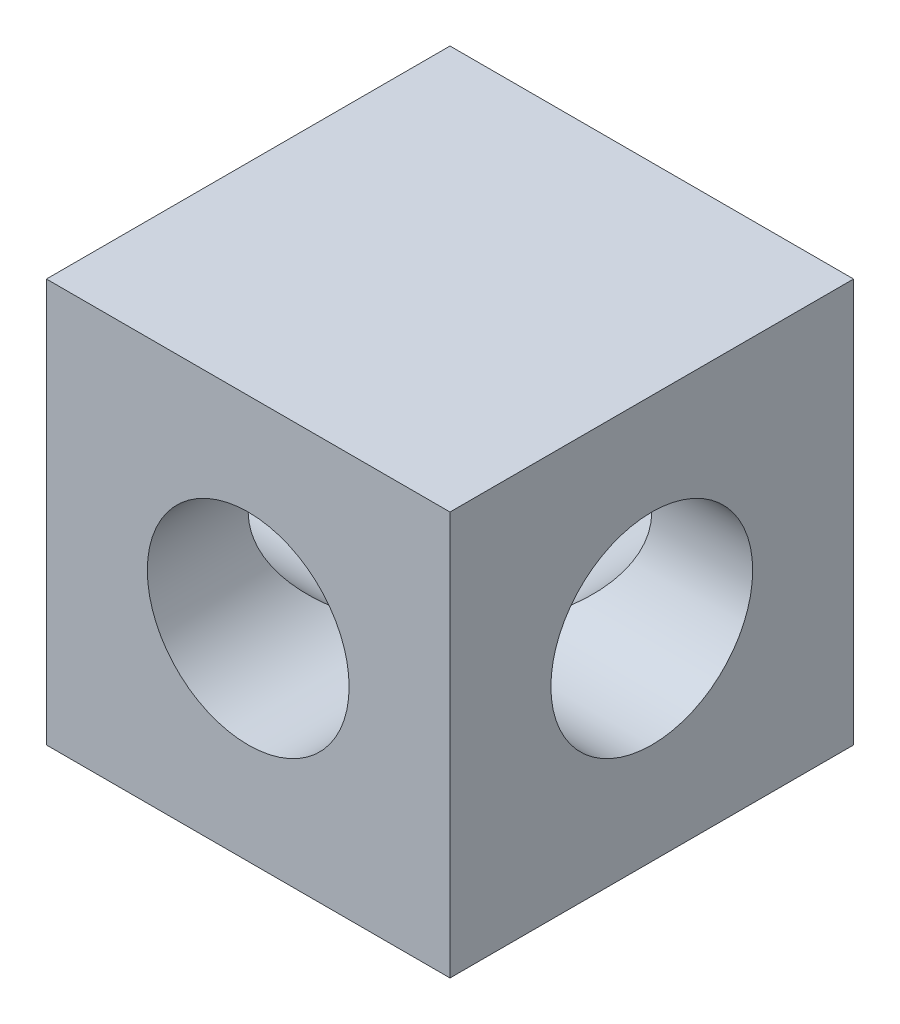
SolidWorks part; units mm, degrees
ref_plane "Front" through (0, 0, 0) normal (0, 0, 1) x (1, 0, 0)
ref_plane "Top" through (0, 0, 0) normal (0, 1, 0) x (-1, 0, 0)
ref_plane "Right" through (0, 0, 0) normal (1, 0, 0) x (0, 0, -1)
other "Configuration Table"
sketch "Sketch1" plane through (0, 0, 0) normal (0, 0, 1) x (1, 0, 0)
  line L0 (-9.525, -9.525) -> (9.525, -9.525)
  line L1 (-9.525, -9.525) -> (-9.525, 9.525)
  line L2 (9.525, 9.525) -> (-9.525, 9.525)
  line L3 (9.525, 9.525) -> (9.525, -9.525)
  line L4 (9.525, 9.525) -> (-9.525, -9.525) construction
  circle A0 centre (0, 0) radius 4.7625
extrude "Base-Extrude" add sketch "Sketch1" along normal mid plane 19.05
sketch "Sketch3" plane through (9.525, 0, 0) normal (1, 0, 0) x (0, 0, -1)
  circle A0 centre (0, 0) radius 4.7625
extrude "Cut-Extrude1" cut sketch "Sketch3" against normal through all
